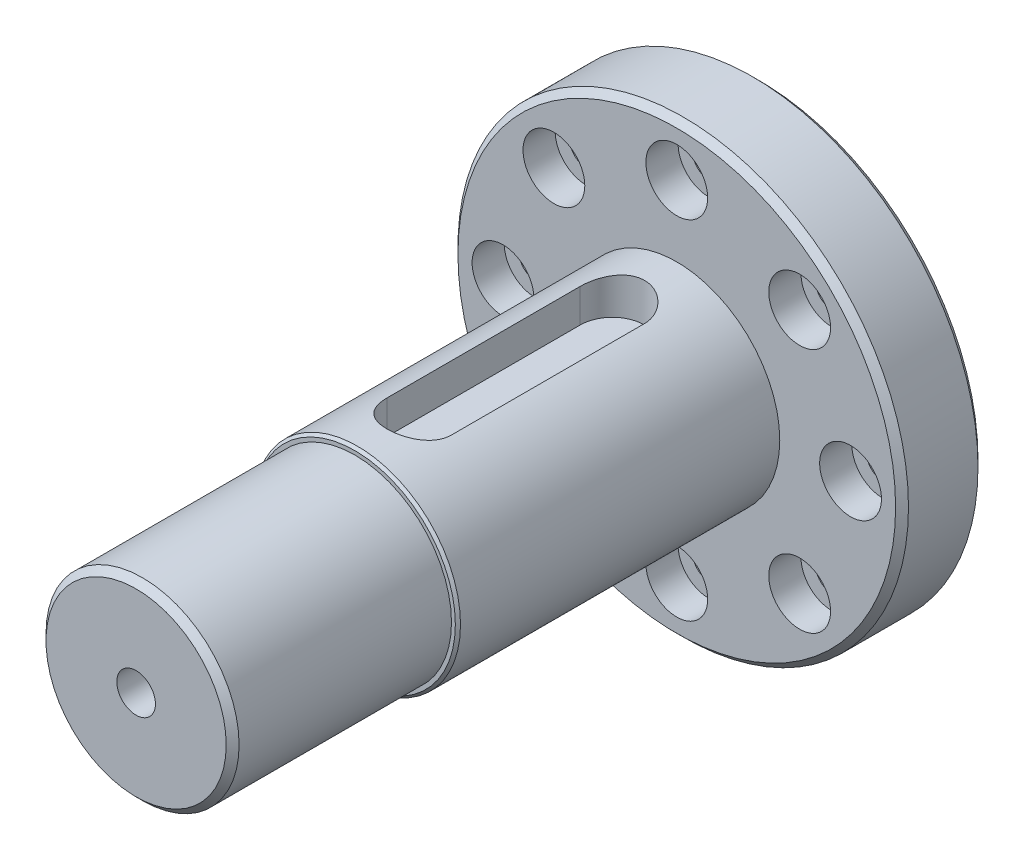
SolidWorks part; units mm, degrees
ref_plane "前视基准面" through (0, 0, 0) normal (0, 0, 1) x (1, 0, 0)
ref_plane "上视基准面" through (0, 0, 0) normal (0, 1, 0) x (1, 0, 0)
ref_plane "右视基准面" through (0, 0, 0) normal (1, 0, 0) x (0, 0, -1)
other "Configuration Table"
sketch "草图1" plane through (0, 0, 0) normal (0, 0, 1) x (1, 0, 0)
  circle A0 centre (0, 0) radius 17.5
  circle A1 centre (0, 0) radius 13.5 construction
  circle A2 centre (0, 13.5) radius 1.25
  circle A10 centre (9.5459, 9.5459) radius 1.25
  circle A11 centre (13.5, 0) radius 1.25
  circle A12 centre (9.5459, -9.5459) radius 1.25
  circle A13 centre (0, -13.5) radius 1.25
  circle A14 centre (-9.5459, -9.5459) radius 1.25
  circle A15 centre (-13.5, 0) radius 1.25
  circle A16 centre (-9.5459, 9.5459) radius 1.25
  point P18 (0, 0)
  point P22 (0, 0)
  dimension "D1" = 35
  dimension "D2" = 27
  dimension "D3" = 2.5
  dimension "D4" = 8
extrude "凸台-拉伸1" add sketch "草图1" along normal blind 6.4
sketch "草图2" plane through (0, 0, 6.4) normal (0, 0, 1) x (1, 0, 0)
  circle A0 centre (0, 0) radius 8
extrude "凸台-拉伸2" add sketch "草图2" along normal blind 42
ref_plane "基准面1" through (0, 8, 0) normal (0, 1, 0) x (1, 0, 0)
sketch "草图6" plane through (0, 8, 0) normal (0, 1, 0) x (1, 0, 0)
  line L0 (0, -48.4) -> (0, -6.4) construction
  line L6 (-2.5, -11.4) -> (-2.5, -26.4)
  line L7 (2.5, -11.4) -> (2.5, -26.4)
  line L9 (-8, -6.4) -> (8, -6.4) construction
  arc A2 (2.5, -11.4) -> (-2.5, -11.4) centre (0, -11.4) ccw
  arc A3 (-2.5, -26.4) -> (2.5, -26.4) centre (0, -26.4) ccw
  point P0 (0, -15.3)
  dimension "D4" = 5
  dimension "D1" = 5
  dimension "D2" = 5
  dimension "D3" = 15
extrude "切除-拉伸1" cut sketch "草图6" against normal blind 3
sketch "草图11" plane through (0, 0, 48.4) normal (0, 0, 1) x (1, 0, 0)
  circle A0 centre (0, 0) radius 1.5
  dimension "D1" = 3
extrude "切除-拉伸4" cut sketch "草图11" against normal blind 5
sketch "草图12" plane through (0, 0, 48.4) normal (0, 0, 1) x (1, 0, 0)
  circle A0 centre (0, 0) radius 7.5
  dimension "D1" = 15
extrude "切除-拉伸5" cut sketch "草图12" against normal blind 17 flip side to cut
chamfer "倒角1" distance 0.5 angle 45 1 edges at (7.5, 0, 48.4)
chamfer "倒角2" distance 0.2 angle 45 1 edges at (8, 0, 31.4)
sketch "草图39" plane through (0, 0, 6.4) normal (0, 0, 1) x (1, 0, 0)
  circle A0 centre (-9.5459, 9.5459) radius 2.4
  circle A1 centre (0, 13.5) radius 2.4
  circle A2 centre (9.5459, 9.5459) radius 2.4
  circle A3 centre (13.5, 0) radius 2.4
  circle A4 centre (9.5459, -9.5459) radius 2.4
  circle A5 centre (0, -13.5) radius 2.4
  circle A6 centre (-9.5459, -9.5459) radius 2.4
  circle A7 centre (-13.5, 0) radius 2.4
  point P19 (0, 0)
  dimension "D1" = 4.8
  dimension "D2" = 8
extrude "切除-拉伸8" cut sketch "草图39" against normal blind 2.5
chamfer "倒角3" distance 0.5 angle 45 2 edges at (17.5, 0, 6.4) (17.5, 0, 0)
sketch "草图40" plane through (0, 0, 0) normal (0, 0, -1) x (-1, 0, 0)
  circle A0 centre (0, 0) radius 10.5
  dimension "D1" = 21
extrude "切除-拉伸9" cut sketch "草图40" against normal blind 2
chamfer "倒角4" distance 0.5 angle 45 1 edges at (-10.5, 0, 0)
